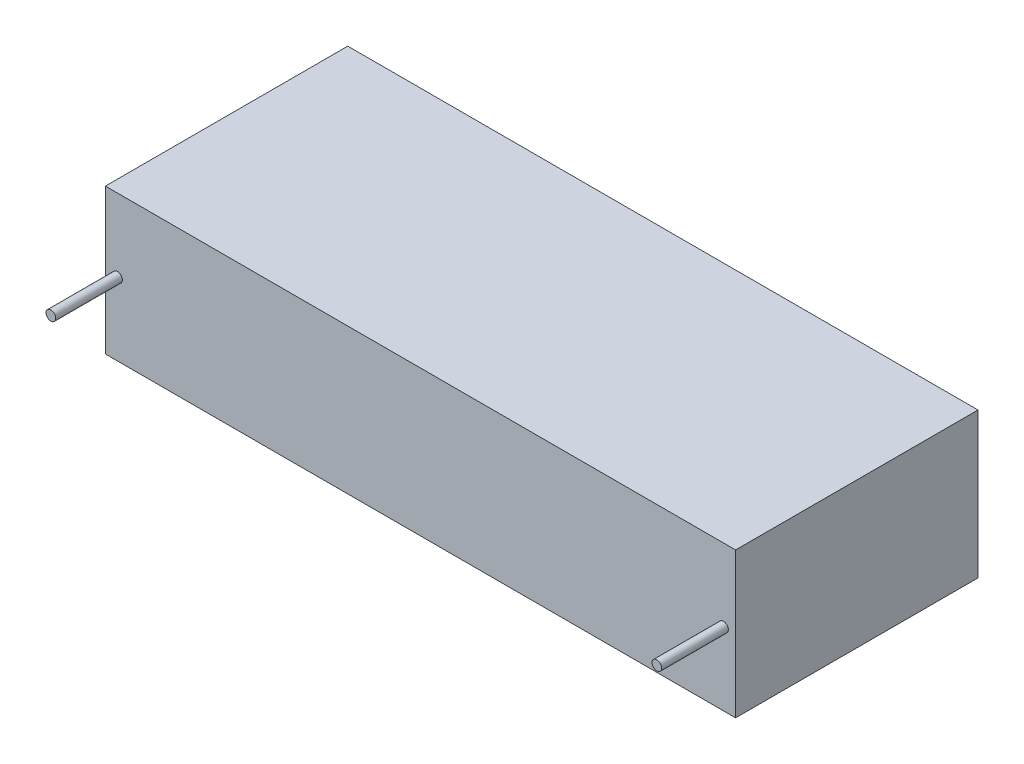
SolidWorks part; units mm, degrees
ref_plane "Спереди" through (0, 0, 0) normal (0, 0, 1) x (1, 0, 0)
ref_plane "Сверху" through (0, 0, 0) normal (0, 1, 0) x (1, 0, 0)
ref_plane "Справа" through (0, 0, 0) normal (1, 0, 0) x (0, 0, -1)
sketch "Эскиз1" plane through (0, 0, 0) normal (0, 0, 1) x (1, 0, 0)
  line L1 (0, 0) -> (52, 0)
  line L2 (0, 0) -> (0, 12)
  line L3 (0, 12) -> (52, 12)
  line L4 (52, 0) -> (52, 12)
  dimension "D1" = 12
  dimension "D2" = 52
extrude "Вытянуть1" add sketch "Эскиз1" along normal blind 20
sketch "Эскиз2" plane through (0, 0, 20) normal (0, 0, 1) x (1, 0, 0)
  line L0 (-0.6613, 6) -> (24.2043, 6) construction
  line L1 (0, 0) -> (52, 0) construction
  line L2 (52, 12) -> (0, 12) construction
  line L3 (26, 10.4113) -> (26, -0.9059) construction
  line L4 (0, 12) -> (0, 0) construction
  line L5 (52, 0) -> (52, 12) construction
  circle A0 centre (1, 6) radius 0.4
  circle A1 centre (51, 6) radius 0.4
  dimension "D1" = 50
  dimension "D2" = 0.8
extrude "Вытянуть2" add sketch "Эскиз2" along normal blind 5.5
